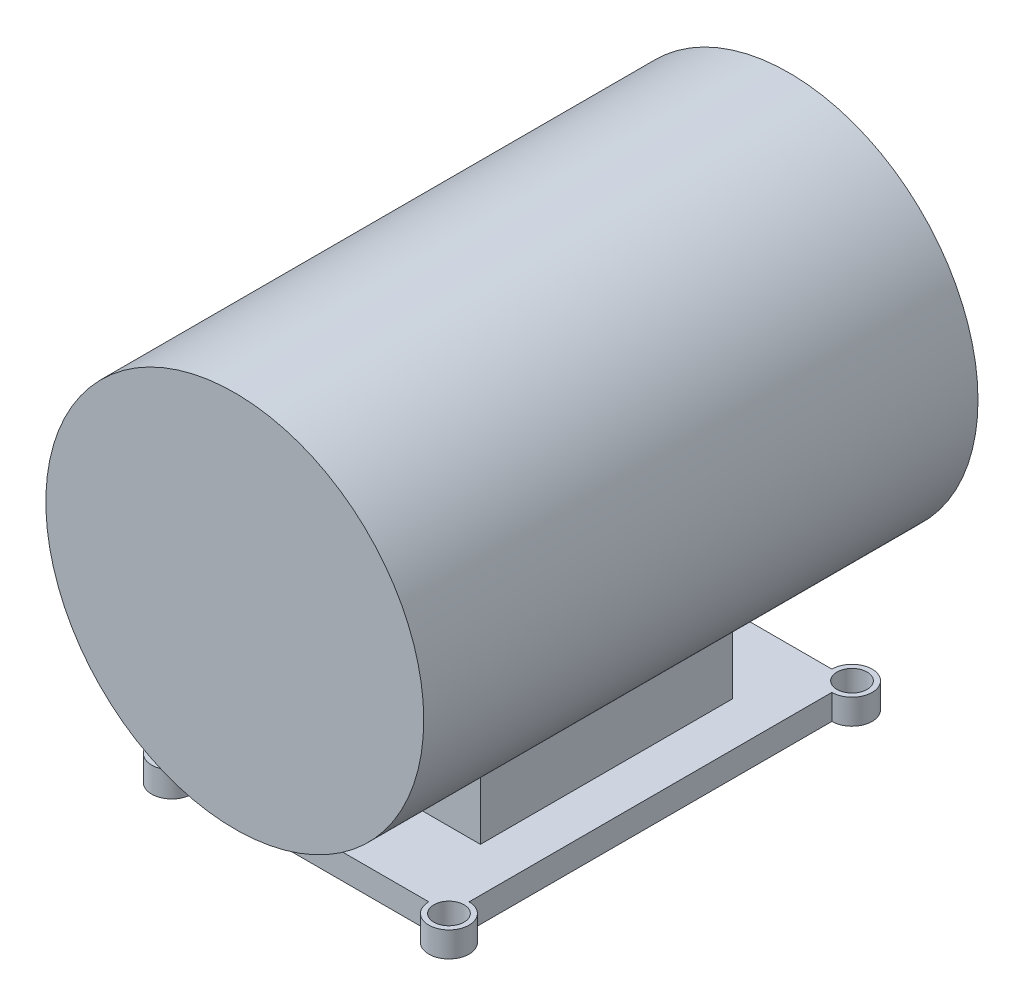
SolidWorks part; units mm, degrees
ref_plane "Front Plane" through (0, 0, 0) normal (0, 0, 1) x (1, 0, 0)
ref_plane "Top Plane" through (0, 0, 0) normal (0, 1, 0) x (1, 0, 0)
ref_plane "Right Plane" through (0, 0, 0) normal (1, 0, 0) x (0, 0, -1)
sketch "Sketch1" plane through (0, 0, 0) normal (0, 1, 0) x (1, 0, 0)
  line L1 (-47, 80) -> (47, 80)
  line L2 (-55, 72) -> (-55, -72)
  line L3 (-47, -80) -> (47, -80)
  line L5 (-1000, 0) -> (49000, 0) construction
  line L8 (55, 72) -> (55, -72)
  circle A0 centre (55, 80) radius 6
  arc A1 (55, 72) -> (47, 80) centre (55, 80) ccw
  circle A2 centre (-55, 80) radius 6
  arc A3 (-47, 80) -> (-55, 72) centre (-55, 80) ccw
  circle A4 centre (55, -80) radius 6
  arc A5 (55, -72) -> (47, -80) centre (55, -80) cw
  arc A6 (-47, -80) -> (-55, -72) centre (-55, -80) cw
  circle A7 centre (-55, -80) radius 6
  point P0 (0, 0)
  dimension "D3" = 12
  dimension "D4" = 16
  dimension "D5" = 12
  dimension "D6" = 16
  dimension "D1" = 110
  dimension "D2" = 160
extrude "Boss-Extrude1" add sketch "Sketch1" along normal mid plane 10
sketch "Sketch2" plane through (0, 5, 0) normal (0, 1, 0) x (1, 0, 0)
  line L1 (-37.5, 50) -> (37.5, 50)
  line L2 (-37.5, 50) -> (-37.5, -50)
  line L3 (-37.5, -50) -> (37.5, -50)
  line L4 (37.5, 50) -> (37.5, -50)
  line L5 (-37.5, 50) -> (37.5, -50) construction
  line L6 (-37.5, -50) -> (37.5, 50) construction
  point P0 (0, 0)
  dimension "D1" = 100
  dimension "D2" = 75
extrude "Boss-Extrude2" add sketch "Sketch2" along normal blind 30
sketch "Sketch3" plane through (0, 0, 50) normal (0, 0, 1) x (1, 0, 0)
  line L0 (-47, -5) -> (47, -5) construction
  circle A0 centre (0, 96.5) radius 75
  dimension "D2" = 150
  dimension "D1" = 101.5
extrude "Boss-Extrude3" add sketch "Sketch3" along normal blind 60 and the other way blind 160
